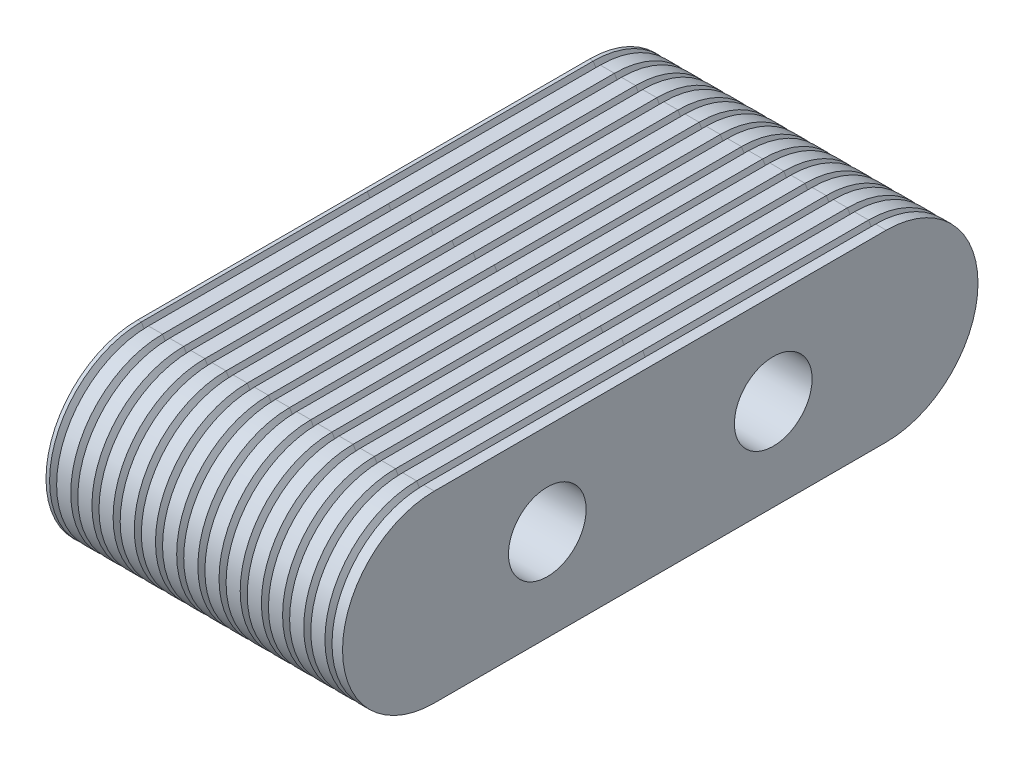
SolidWorks part; units mm, degrees
ref_plane "Front Plane" through (0, 0, 0) normal (0, 0, 1) x (1, 0, 0)
ref_plane "Top Plane" through (0, 0, 0) normal (0, 1, 0) x (1, 0, 0)
ref_plane "Right Plane" through (0, 0, 0) normal (1, 0, 0) x (0, 0, -1)
sketch "Sketch2" plane through (0, 0, 0) normal (1, 0, 0) x (0, 0, -1)
  line L0 (16, 0) -> (-16, 0) construction
  line L1 (16, -8) -> (-16, -8) construction
  line L2 (16, 8) -> (-16, 8) construction
  line L3 (16, -6.5) -> (-16, -6.5)
  line L4 (16, 6.5) -> (-16, 6.5)
  arc A0 (16, -8) -> (16, 8) centre (16, 0) ccw construction
  arc A1 (-16, 8) -> (-16, -8) centre (-16, 0) ccw construction
  arc A2 (-16, 6.5) -> (-16, -6.5) centre (-16, 0) ccw
  arc A3 (16, -6.5) -> (16, 6.5) centre (16, 0) ccw
  point P2 (0, 0)
  dimension "D1" = 32
  dimension "D2" = 16
  dimension "D3" = 1.5
extrude "Boss-Extrude1" add sketch "Sketch2" along normal mid plane 21
sketch "Sketch3" plane through (0, 0, 0) normal (0, 0, 1) x (1, 0, 0)
  line L0 (-10.2475, 6.5) -> (-9.9975, 6.067)
  line L1 (-9.9975, 6.067) -> (-9.7475, 6.5)
  line L2 (-9.7475, 6.5) -> (-10.2475, 6.5)
  line L4 (10.5, 6.5) -> (-10.5, 6.5) construction
  dimension "D1" = 0.5
  dimension "D2" = 0.2525
sketch "Sketch4" plane through (-10.5, 0, 0) normal (-1, 0, 0) x (0, 0, 1)
  line L6 (-16, -6.5) -> (16, -6.5)
  line L7 (16, 6.5) -> (-16, 6.5)
  line L8 (-16, -6.5) -> (16, -6.5)
  line L9 (16, 6.5) -> (-16, 6.5)
  arc A6 (-16, 6.5) -> (-16, -6.5) centre (-16, 0) ccw
  arc A7 (16, -6.5) -> (16, 6.5) centre (16, 0) ccw
  arc A8 (-16, 6.5) -> (-16, -6.5) centre (-16, 0) ccw
  arc A9 (16, -6.5) -> (16, 6.5) centre (16, 0) ccw
  dimension "D1" = 0
sweep "Cut-Sweep1" cut profiles "Sketch3" path "Sketch4"
pattern_linear "LPattern1" count 14 spacing 1.5 along (1, 0, 0) of "Cut-Sweep1"
sketch "Sketch5" plane through (10.5, 0, 0) normal (1, 0, 0) x (0, 0, -1)
  line L0 (-8, 0) -> (8, 0) construction
  circle A0 centre (-8, 0) radius 2.75
  circle A1 centre (8, 0) radius 2.75
  point P4 (0, 0)
  dimension "D1" = 5.5
  dimension "D2" = 16
extrude "Cut-Extrude1" cut sketch "Sketch5" against normal through all both and the other way through all
